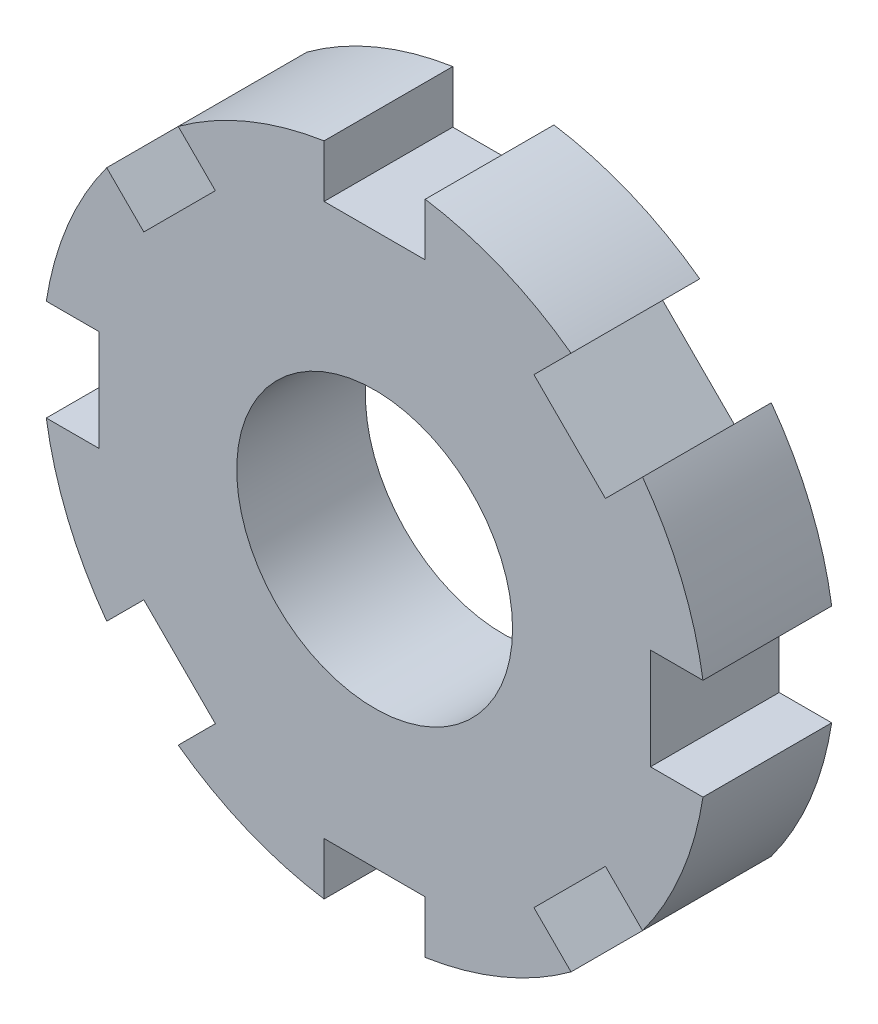
SolidWorks part; units mm, degrees
ref_plane "Plan de face" through (0, 0, 0) normal (0, 0, 1) x (1, 0, 0)
ref_plane "Plan de dessus" through (0, 0, 0) normal (0, 1, 0) x (1, 0, 0)
ref_plane "Plan de droite" through (0, 0, 0) normal (1, 0, 0) x (0, 0, -1)
sketch "Esquisse1" plane through (0, 0, 0) normal (0, 0, 1) x (1, 0, 0)
  line L0 (-5.5, 0) -> (5.5, 0)
  line L1 (5.5, 0) -> (5.5, -15)
  line L2 (5.5, -15) -> (21.3609, 0.8609)
  line L3 (21.3609, 0.8609) -> (17.3241, 4.8977)
  line L4 (17.3241, 4.8977) -> (25.1023, 12.6759)
  line L5 (21.2132, 8.7868) -> (0, 30) construction
  line L6 (29.1391, 8.6391) -> (25.1023, 12.6759)
  line L7 (45, 24.5) -> (29.1391, 8.6391)
  line L8 (30, 24.5) -> (45, 24.5)
  line L9 (0, 0) -> (0, 60) construction
  line L10 (-30, 30) -> (30, 30) construction
  line L11 (30, 35.5) -> (30, 24.5)
  line L12 (21.2132, 51.2132) -> (0, 30) construction
  line L13 (30, 35.5) -> (45, 35.5)
  line L14 (45, 35.5) -> (29.1391, 51.3609)
  line L15 (29.1391, 51.3609) -> (25.1023, 47.3241)
  line L16 (17.3241, 55.1023) -> (25.1023, 47.3241)
  line L17 (21.3609, 59.1391) -> (17.3241, 55.1023)
  line L18 (5.5, 75) -> (21.3609, 59.1391)
  line L19 (5.5, 60) -> (5.5, 75)
  line L20 (-5.5, 60) -> (5.5, 60)
  line L21 (-21.2132, 51.2132) -> (0, 30) construction
  line L22 (-21.2132, 8.7868) -> (0, 30) construction
  line L23 (-5.5, 60) -> (-5.5, 75)
  line L24 (-5.5, 75) -> (-21.3609, 59.1391)
  line L25 (-21.3609, 59.1391) -> (-17.3241, 55.1023)
  line L26 (-17.3241, 55.1023) -> (-25.1023, 47.3241)
  line L27 (-29.1391, 51.3609) -> (-25.1023, 47.3241)
  line L28 (-45, 35.5) -> (-29.1391, 51.3609)
  line L29 (-30, 35.5) -> (-45, 35.5)
  line L30 (-30, 35.5) -> (-30, 24.5)
  line L31 (-30, 24.5) -> (-45, 24.5)
  line L32 (-45, 24.5) -> (-29.1391, 8.6391)
  line L33 (-29.1391, 8.6391) -> (-25.1023, 12.6759)
  line L34 (-17.3241, 4.8977) -> (-25.1023, 12.6759)
  line L35 (-21.3609, 0.8609) -> (-17.3241, 4.8977)
  line L36 (-5.5, -15) -> (-21.3609, 0.8609)
  line L37 (-5.5, 0) -> (-5.5, -15)
  circle A0 centre (0, 30) radius 30 construction
  point P24 (30, 30)
  dimension "D1" = 60
  dimension "D2" = 11
  dimension "D3" = 15
  dimension "D5" = 5.5
  dimension "D7" = 30
extrude "Boss.-Extru.1" add sketch "Esquisse1" along normal blind 14
sketch "Esquisse2" plane through (0, 0, 14) normal (0, 0, 1) x (1, 0, 0)
  line L0 (0, 0) -> (0, 60) construction
  line L1 (5.5, 60) -> (-5.5, 60) construction
  circle A0 centre (0, 30) radius 15
  dimension "D1" = 30
extrude "Enlèv. mat.-Extru.1" cut sketch "Esquisse2" against normal through all both and the other way through all
sketch "Esquisse3" plane through (0, 0, 14) normal (0, 0, 1) x (1, 0, 0)
  circle A0 centre (0, 30) radius 36.13
  circle A1 centre (0, 30) radius 45.3349
extrude "Enlèv. mat.-Extru.2" cut sketch "Esquisse3" against normal through all
